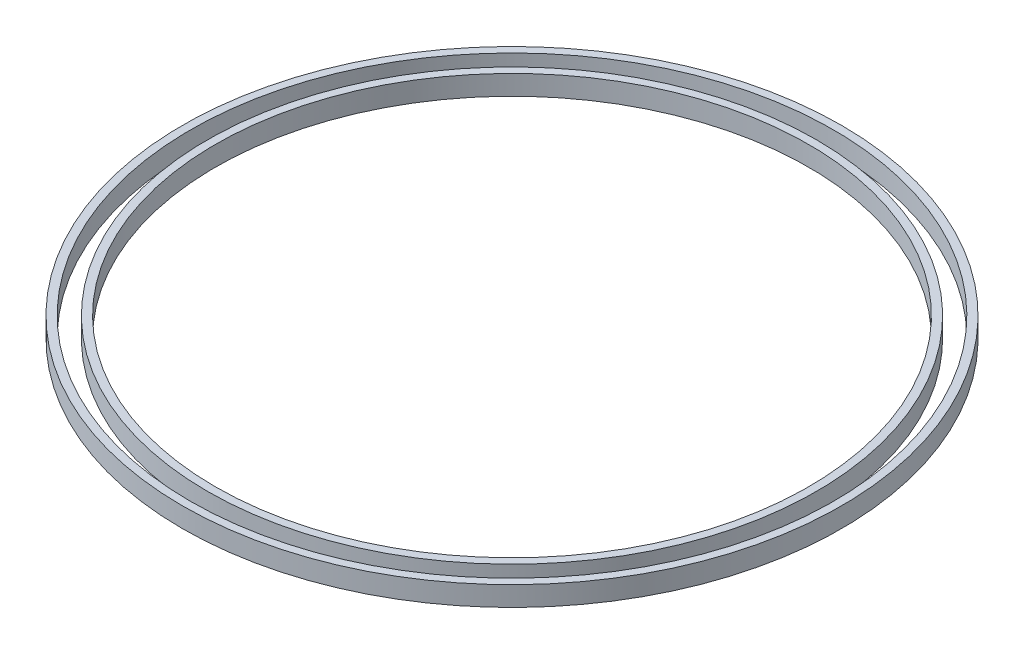
SolidWorks part; units mm, degrees
material "ABS"
ref_plane "Front Plane" through (0, 0, 0) normal (0, 0, 1) x (1, 0, 0)
ref_plane "Top Plane" through (0, 0, 0) normal (0, 1, 0) x (1, 0, 0)
ref_plane "Right Plane" through (0, 0, 0) normal (1, 0, 0) x (0, 0, -1)
sketch "Sketch1" plane through (0, 0, 0) normal (0, 1, 0) x (1, 0, 0)
  circle A0 centre (0, 0) radius 45
  circle A2 centre (0, 0) radius 46.2
extrude "Boss-Extrude1" add sketch "Sketch1" along normal blind 3
sketch "Sketch2" plane through (0, 0, 0) normal (0, 1, 0) x (1, 0, 0)
  circle A0 centre (0, 0) radius 48.8
  circle A1 centre (0, 0) radius 50
extrude "Boss-Extrude2" add sketch "Sketch2" along normal blind 3 separate body
ref_plane "Plane1" through (-50, 0, 0) normal (-1, 0, 0) x (0, 0, 1)
sketch "Sketch3" plane through (-50, 0, 0) normal (-1, 0, 0) x (0, 0, 1)
  line L0 (-50, 0) -> (-50, 0.25) construction
  line L1 (-50, 0.25) -> (50, 0.25) construction
  text T0 "144\r\n" font "Century Gothic" height 2.5
extrude "Cut-Extrude1" cut sketch "Sketch3" against normal blind 0.4
